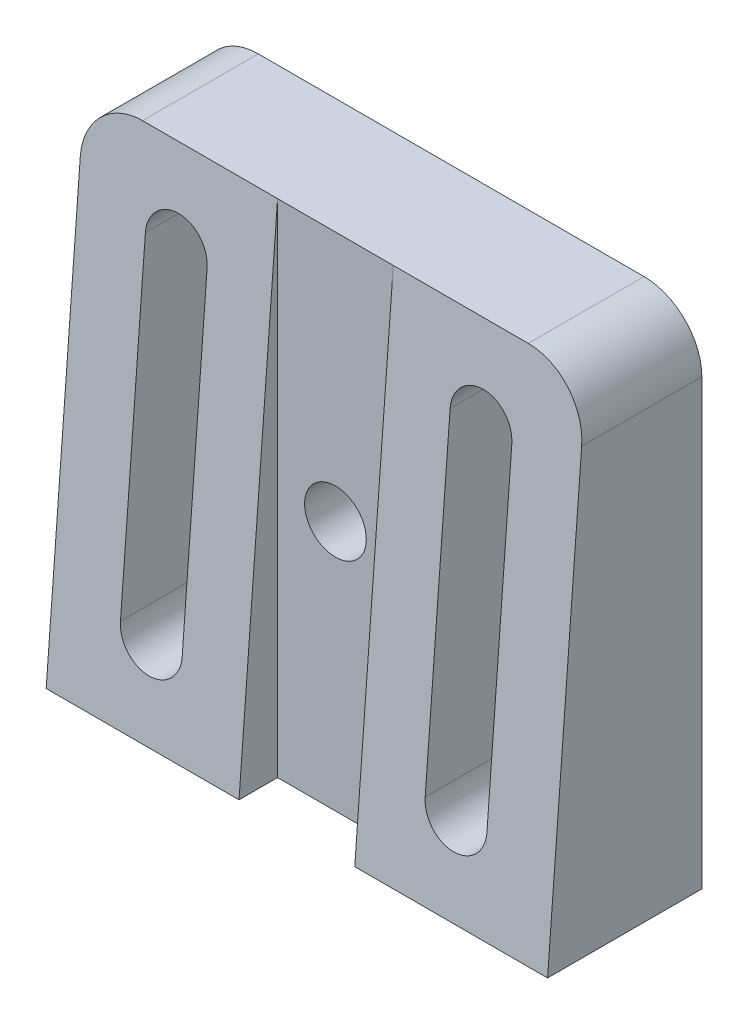
SolidWorks part; units mm, degrees
material "3.1325 (EN-AW 2017A)"
ref_plane "正面" through (0, 0, 0) normal (0, 0, 1) x (1, 0, 0)
ref_plane "平面" through (0, 0, 0) normal (0, 1, 0) x (1, 0, 0)
ref_plane "右側面" through (0, 0, 0) normal (1, 0, 0) x (0, 0, -1)
sketch "ｽｹｯﾁ1" plane through (0, 0, 0) normal (0, 0, 1) x (1, 0, 0)
  line L0 (0, 13) -> (0, -13) construction
  line L1 (-13, 13) -> (13, 13)
  line L2 (-13, 13) -> (-13, -13)
  line L3 (-13, -13) -> (13, -13)
  line L4 (13, 13) -> (13, -13)
  line L5 (-7.9, 8.4) -> (-7.9, -8.4) construction
  line L6 (-6.3, 8.4) -> (-6.3, -8.4)
  line L7 (-9.5, 8.4) -> (-9.5, -8.4)
  line L8 (7.9, 8.4) -> (7.9, -8.4) construction
  line L9 (9.5, 8.4) -> (9.5, -8.4)
  line L10 (6.3, 8.4) -> (6.3, -8.4)
  arc A0 (-6.3, 8.4) -> (-9.5, 8.4) centre (-7.9, 8.4) ccw
  arc A1 (-9.5, -8.4) -> (-6.3, -8.4) centre (-7.9, -8.4) ccw
  arc A2 (9.5, 8.4) -> (6.3, 8.4) centre (7.9, 8.4) ccw
  arc A3 (6.3, -8.4) -> (9.5, -8.4) centre (7.9, -8.4) ccw
  point P6 (0, 0)
  point P10 (-7.9, 0)
  point P15 (7.9, 0)
  dimension "D1" = 26
  dimension "D2" = 15.8
  dimension "D3" = 3.2
  dimension "D4" = 3
extrude "ﾎﾞｽ - 押し出し1" add sketch "ｽｹｯﾁ1" along normal blind 8
sketch "ｽｹｯﾁ2" plane through (0, 0, 0) normal (1, 0, 0) x (0, 0, -1)
  line L0 (0, -13) -> (-8, -13)
  line L1 (-8, -13) -> (-6, 13)
  line L2 (-8, 13) -> (0, 13) construction
  line L3 (-6, 13) -> (0, 13)
  line L4 (0, 13) -> (0, -13)
  dimension "D1" = 6
extrude "ｶｯﾄ - 押し出し1" cut sketch "ｽｹｯﾁ2" against normal through all both and the other way through all flip side to cut
hole_wizard "M3 すきま穴1" positions "3Dｽｹｯﾁ1" profile "ｽｹｯﾁ3" hole size "M3" standard "JIS" end condition through all
sketch3d "3Dｽｹｯﾁ1"
  point P0 (0, 0, 0)
sketch "ｽｹｯﾁ3" plane through (0, 0, 0) normal (1, 0, 0) x (0, 1, 0)
  line L0 (0, 0) -> (0, 8)
  line L1 (0, 8) -> (1.6, 8)
  line L2 (1.6, 8) -> (1.6, 0)
  line L5 (1.6, 0) -> (0, 0)
  line L11 (0, -6.35) -> (0, 107.95) construction
  dimension "通し穴の直径" = 3.2
  dimension "通し穴の深さ" = 8
sketch "ｽｹｯﾁ4" plane through (0, 0, 0) normal (1, 0, 0) x (0, 0, -1)
  line L1 (0, -13) -> (-6, -13)
  line L2 (0, -13) -> (0, 13)
  line L3 (0, 13) -> (-6, 13)
  line L4 (-6, -13) -> (-6, 13)
extrude "ｶｯﾄ - 押し出し2" cut sketch "ｽｹｯﾁ4" against normal mid plane 6 flip side to cut
fillet "ﾌｨﾚｯﾄ1" radius 3 2 edges at (13, 13, 3) (-13, 13, 3)
